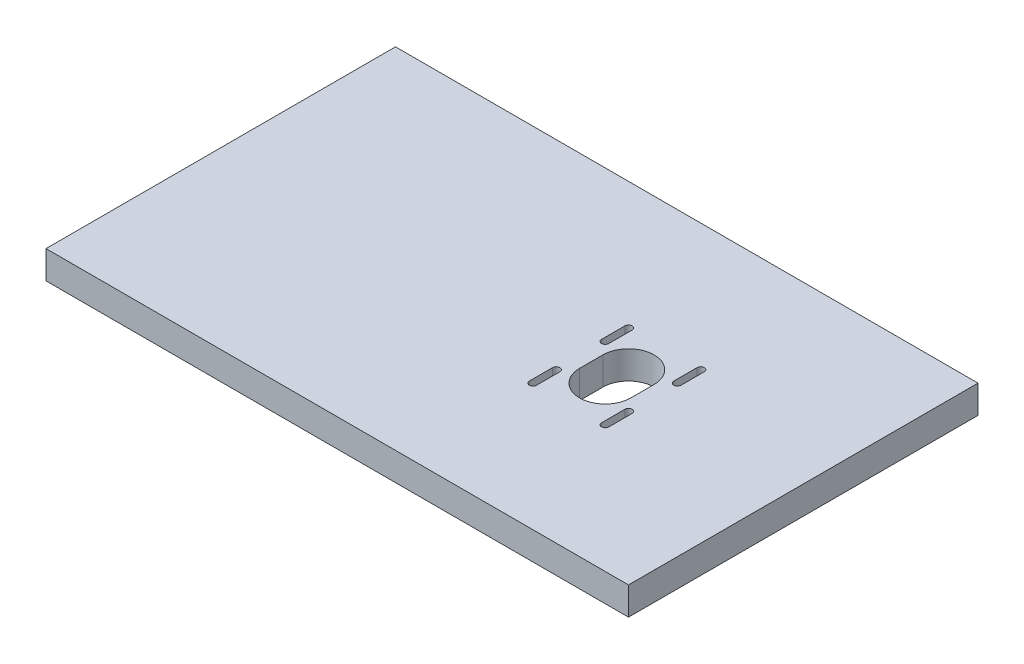
SolidWorks part; units mm, degrees
ref_plane "Ebene vorne" through (0, 0, 0) normal (0, 0, 1) x (1, 0, 0)
ref_plane "Ebene oben" through (0, 0, 0) normal (0, 1, 0) x (1, 0, 0)
ref_plane "Ebene rechts" through (0, 0, 0) normal (1, 0, 0) x (0, 0, -1)
sketch "Skizze1" plane through (0, 0, 0) normal (0, 1, 0) x (1, 0, 0)
  line L0 (29.5, 10.5) -> (29.5, 20.5) construction
  line L1 (-125, 75) -> (125, 75)
  line L2 (-125, 75) -> (-125, -75)
  line L3 (-125, -75) -> (125, -75)
  line L4 (125, 75) -> (125, -75)
  line L5 (-125, 75) -> (125, -75) construction
  line L6 (-125, -75) -> (125, 75) construction
  line L7 (29.5, 15.5) -> (60.5, 15.5) construction
  line L8 (29.5, 15.5) -> (29.5, -15.5) construction
  line L9 (29.5, -15.5) -> (60.5, -15.5) construction
  line L10 (60.5, 15.5) -> (60.5, -15.5) construction
  line L11 (29.5, 15.5) -> (60.5, -15.5) construction
  line L12 (29.5, -15.5) -> (60.5, 15.5) construction
  line L13 (27.95, 10.5) -> (27.95, 20.5)
  line L14 (31.05, 10.5) -> (31.05, 20.5)
  line L15 (60.5, 20.5) -> (60.5, 10.5) construction
  line L16 (62.05, 20.5) -> (62.05, 10.5)
  line L17 (58.95, 20.5) -> (58.95, 10.5)
  line L18 (60.5, -20.5) -> (60.5, -10.5) construction
  line L19 (58.95, -20.5) -> (58.95, -10.5)
  line L20 (62.05, -20.5) -> (62.05, -10.5)
  line L21 (29.5, -20.5) -> (29.5, -10.5) construction
  line L22 (27.95, -20.5) -> (27.95, -10.5)
  line L23 (31.05, -20.5) -> (31.05, -10.5)
  line L24 (29.5, 0) -> (60.5, 0) construction
  line L25 (45, 5) -> (45, -5) construction
  line L26 (56, 5) -> (56, -5)
  line L27 (34, 5) -> (34, -5)
  line L28 (45, 15.5) -> (45, -15.5) construction
  arc A0 (27.95, 10.5) -> (31.05, 10.5) centre (29.5, 10.5) ccw
  arc A1 (31.05, 20.5) -> (27.95, 20.5) centre (29.5, 20.5) ccw
  arc A2 (62.05, 20.5) -> (58.95, 20.5) centre (60.5, 20.5) ccw
  arc A3 (58.95, 10.5) -> (62.05, 10.5) centre (60.5, 10.5) ccw
  arc A4 (58.95, -20.5) -> (62.05, -20.5) centre (60.5, -20.5) ccw
  arc A5 (62.05, -10.5) -> (58.95, -10.5) centre (60.5, -10.5) ccw
  arc A6 (27.95, -20.5) -> (31.05, -20.5) centre (29.5, -20.5) ccw
  arc A7 (31.05, -10.5) -> (27.95, -10.5) centre (29.5, -10.5) ccw
  arc A8 (56, 5) -> (34, 5) centre (45, 5) ccw
  arc A9 (34, -5) -> (56, -5) centre (45, -5) ccw
  point P0 (0, 0)
  point P5 (45, 0)
  point P13 (29.5, 15.5)
  point P20 (60.5, 15.5)
  point P26 (60.5, -15.5)
  point P33 (29.5, -15.5)
  point P42 (45, 0)
  point P52 (-125, 0)
  dimension "D1" = 250
  dimension "D2" = 150
  dimension "D3" = 31
  dimension "D4" = 31
  dimension "D5" = 3.1
  dimension "D6" = 3.1
  dimension "D7" = 3.1
  dimension "D8" = 3.1
  dimension "D9" = 22
  dimension "D10" = 5
  dimension "D11" = 5
  dimension "D12" = 5
  dimension "D13" = 5
  dimension "D14" = 5
  dimension "D15" = 80
extrude "Aufsatz-Linear austragen1" add sketch "Skizze1" along normal blind 12
